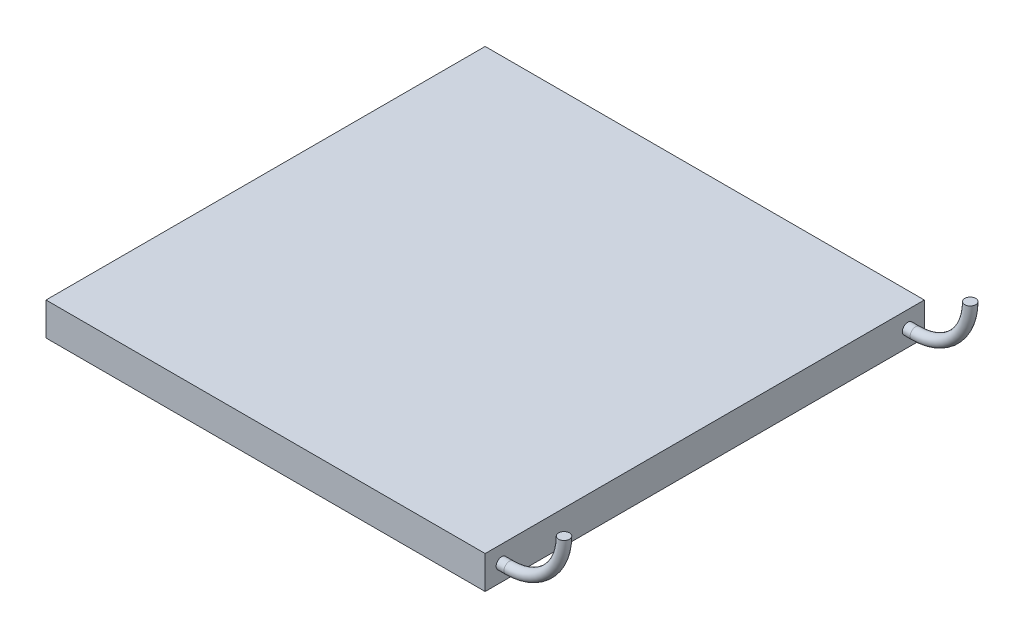
SolidWorks part; units mm, degrees
ref_plane "Front Plane" through (0, 0, 0) normal (0, 0, 1) x (1, 0, 0)
ref_plane "Top Plane" through (0, 0, 0) normal (0, 1, 0) x (1, 0, 0)
ref_plane "Right Plane" through (0, 0, 0) normal (1, 0, 0) x (0, 0, -1)
sketch "Sketch1" plane through (0, 0, 0) normal (0, 1, 0) x (1, 0, 0)
  line L1 (-20, -20) -> (20, -20)
  line L2 (-20, -20) -> (-20, 20)
  line L3 (-20, 20) -> (20, 20)
  line L4 (20, -20) -> (20, 20)
  line L5 (-20, -20) -> (20, 20) construction
  line L6 (-20, 20) -> (20, -20) construction
  point P0 (0, 0)
  dimension "D1" = 40
extrude "Boss-Extrude1" add sketch "Sketch1" along normal blind 3
sketch "Sketch2" plane through (20, 0, 0) normal (1, 0, 0) x (0, 0, -1)
  line L1 (-17, 0) -> (-20, 0) construction
  line L2 (-17, 0) -> (-17, 3) construction
  line L3 (-17, 3) -> (-20, 3) construction
  line L4 (-20, 0) -> (-20, 3) construction
  line L5 (-17, 0) -> (-20, 3) construction
  line L6 (-17, 3) -> (-20, 0) construction
  circle A0 centre (-18.5, 1.5) radius 0.5
  point P0 (-18.5, 1.5)
  dimension "D1" = 1
ref_plane "Plane1" through (0, 0, 18.5) normal (0, 0, 1) x (1, 0, 0)
sketch "Sketch3" plane through (0, 0, 18.5) normal (0, 0, 1) x (1, 0, 0)
  line L0 (20, 1.5) -> (20.711, 1.5)
  arc A0 (20.711, 1.5) -> (25.6815, 6.4705) centre (20.711, 6.4705) ccw
sweep "Sweep1" add profiles "Sketch2" path "Sketch3"
mirror "Mirror1" about plane through (0, 0, 0) normal (0, 0, 1) of "Sweep1"
